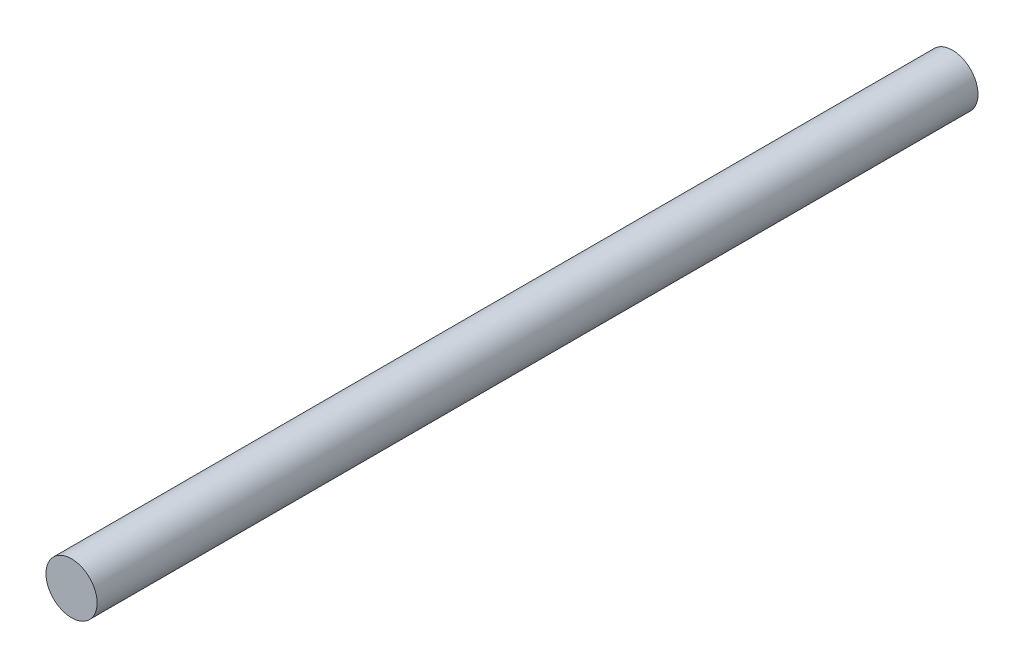
SolidWorks part; units mm, degrees
material "PP Copolymer"
ref_plane "Frontal" through (0, 0, 0) normal (0, 0, 1) x (1, 0, 0)
ref_plane "Superior " through (0, 0, 0) normal (0, 1, 0) x (1, 0, 0)
ref_plane "Lateral" through (0, 0, 0) normal (1, 0, 0) x (0, 0, -1)
sketch "Sketch1" plane through (0, 0, 0) normal (0, 0, 1) x (1, 0, 0)
  circle A0 centre (0, 0) radius 2.7
  dimension "D1" = 5.4
extrude "Base-Extrude" add sketch "Sketch1" against normal blind 93
